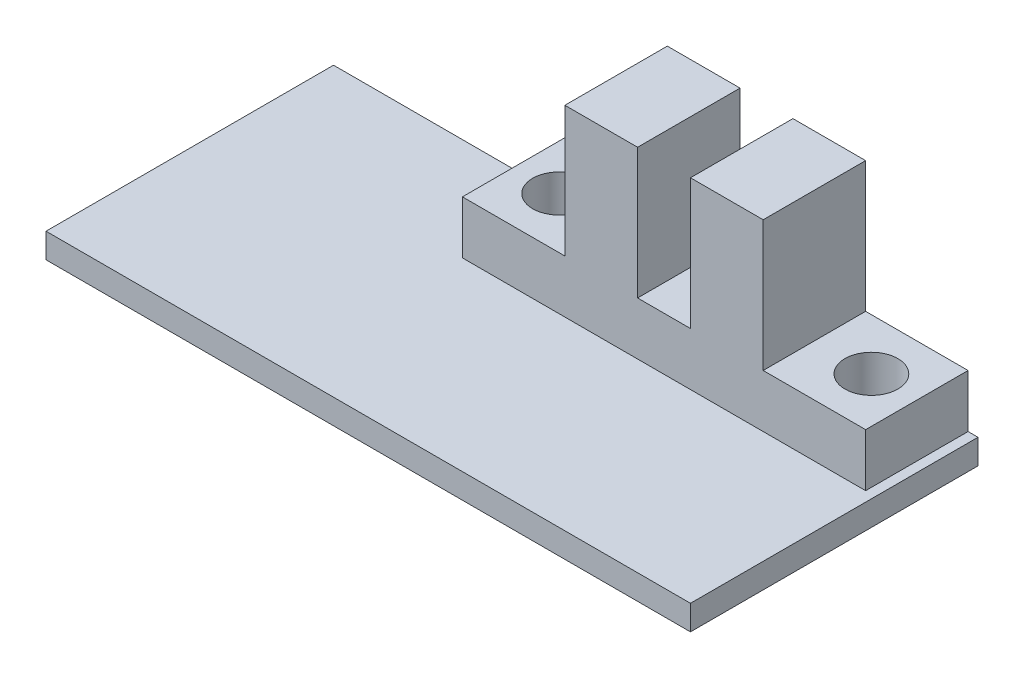
SolidWorks part; units mm, degrees
ref_plane "Front Plane" through (0, 0, 0) normal (0, 0, 1) x (1, 0, 0)
ref_plane "Top Plane" through (0, 0, 0) normal (0, 1, 0) x (1, 0, 0)
ref_plane "Right Plane" through (0, 0, 0) normal (1, 0, 0) x (0, 0, -1)
sketch "Sketch1" plane through (0, 0, 0) normal (0, 1, 0) x (1, 0, 0)
  line L1 (-19.5, 8.7) -> (19.5, 8.7)
  line L2 (-19.5, 8.7) -> (-19.5, -8.7)
  line L3 (-19.5, -8.7) -> (19.5, -8.7)
  line L4 (19.5, 8.7) -> (19.5, -8.7)
  line L5 (-19.5, 8.7) -> (19.5, -8.7) construction
  line L6 (-19.5, -8.7) -> (19.5, 8.7) construction
  point P0 (0, 0)
  dimension "D1" = 39
  dimension "D2" = 17.4
extrude "Boss-Extrude1" add sketch "Sketch1" along normal blind 1.5
sketch "Sketch2" plane through (0, 1.5, 0) normal (0, 1, 0) x (1, 0, 0)
  line L0 (19.5, 8.7) -> (-19.5, 8.7) construction
  line L1 (-5.5, 8.7) -> (18.9, 8.7)
  line L2 (-5.5, 8.7) -> (-5.5, 2.5)
  line L3 (-5.5, 2.5) -> (18.9, 2.5)
  line L4 (18.9, 8.7) -> (18.9, 2.5)
  line L5 (19.5, -8.7) -> (19.5, 8.7) construction
  dimension "D1" = 0.6
  dimension "D2" = 6.2
  dimension "D3" = 24.4
extrude "Boss-Extrude2" add sketch "Sketch2" along normal blind 3.2
sketch "Sketch3" plane through (0, 4.7, 0) normal (0, 1, 0) x (1, 0, 0)
  line L0 (18.9, 8.7) -> (-5.5, 8.7) construction
  line L1 (0.7, 8.7) -> (5.1, 8.7)
  line L2 (0.7, 8.7) -> (0.7, 2.5)
  line L3 (0.7, 2.5) -> (5.1, 2.5)
  line L4 (5.1, 8.7) -> (5.1, 2.5)
  line L5 (-5.5, 2.5) -> (18.9, 2.5) construction
  line L6 (-5.5, 8.7) -> (-5.5, 2.5) construction
  line L7 (8.3, 8.7) -> (12.7, 8.7)
  line L8 (8.3, 8.7) -> (8.3, 2.5)
  line L9 (8.3, 2.5) -> (12.7, 2.5)
  line L10 (12.7, 8.7) -> (12.7, 2.5)
  dimension "D1" = 4.4
  dimension "D2" = 4.4
  dimension "D3" = 12
  dimension "D4" = 6.2
extrude "Boss-Extrude3" add sketch "Sketch3" along normal blind 7.9
sketch "Sketch4" plane through (0, 4.7, 0) normal (0, 1, 0) x (1, 0, 0)
  line L0 (0.7, 8.7) -> (-5.5, 8.7) construction
  line L1 (18.9, 8.7) -> (12.7, 8.7) construction
  line L2 (-5.5, 8.7) -> (-5.5, 2.5) construction
  line L3 (19.5, -8.7) -> (19.5, 8.7) construction
  circle A0 centre (-2.75, 5.6) radius 1.6
  circle A1 centre (16.15, 5.6) radius 1.6
  dimension "D1" = 3.2
  dimension "D3" = 3.2
  dimension "D2" = 3.1
  dimension "D4" = 3.1
  dimension "D5" = 18.9
  dimension "D6" = 2.75
extrude "Cut-Extrude1" cut sketch "Sketch4" against normal through all
